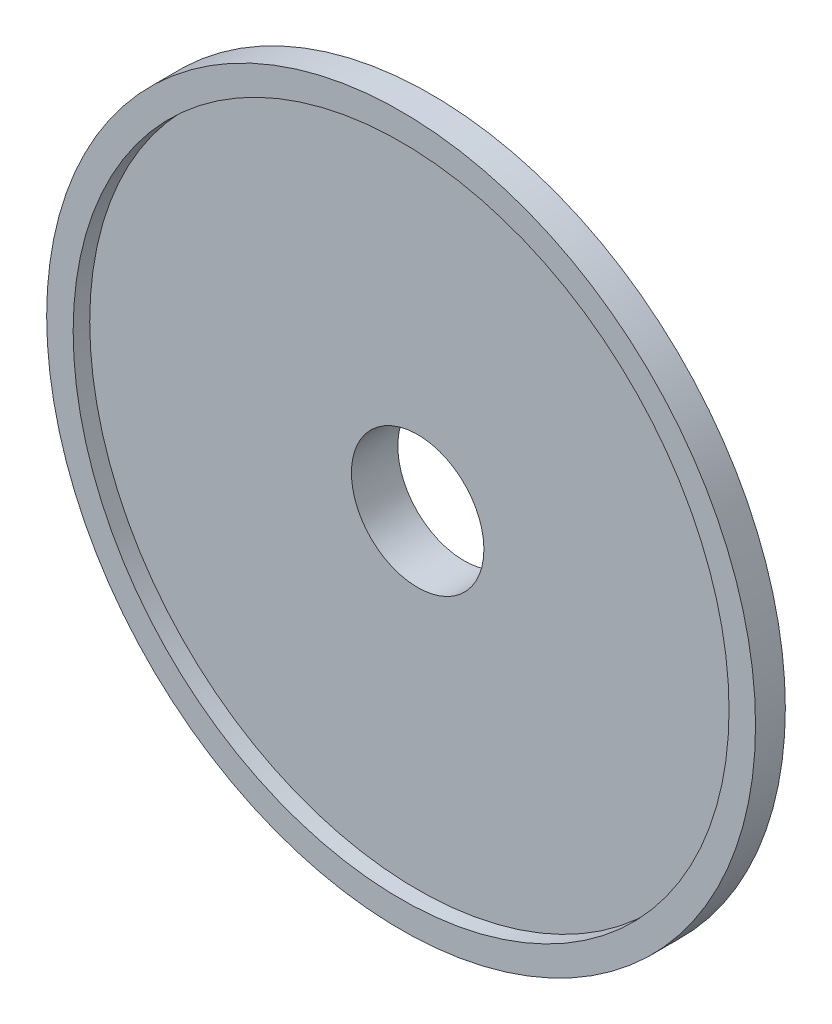
SolidWorks part; units mm, degrees
ref_plane "Front Plane" through (0, 0, 0) normal (0, 0, 1) x (1, 0, 0)
ref_plane "Top Plane" through (0, 0, 0) normal (0, 1, 0) x (1, 0, 0)
ref_plane "Right Plane" through (0, 0, 0) normal (1, 0, 0) x (0, 0, -1)
sketch "Sketch1" plane through (0, 0, 0) normal (0, 0, 1) x (1, 0, 0)
  circle A0 centre (0, 0) radius 53.5
extrude "Boss-Extrude1" add sketch "Sketch1" along normal blind 14.5
sketch "Sketch2" plane through (0, 0, 14.5) normal (0, 0, 1) x (1, 0, 0)
  circle A0 centre (0, 0) radius 49.5
extrude "Cut-Extrude1" cut sketch "Sketch2" against normal blind 2.5
sketch "Sketch3" plane through (0, 0, 12) normal (0, 0, 1) x (1, 0, 0)
  circle A0 centre (0, 0) radius 10
extrude "Cut-Extrude3" cut sketch "Sketch3" against normal blind 14.5
sketch "Sketch6" plane through (0, 0, 0) normal (0, 0, -1) x (-1, 0, 0)
  circle A3 centre (0, 0) radius 53.5
  circle A4 centre (0, 0) radius 30
extrude "Cut-Extrude8" cut sketch "Sketch6" against normal blind 10
sketch "Sketch7" plane through (0, 0, 0) normal (0, 0, -1) x (-1, 0, 0)
  circle A0 centre (0, 0) radius 27.8
extrude "Cut-Extrude9" cut sketch "Sketch7" against normal blind 5
